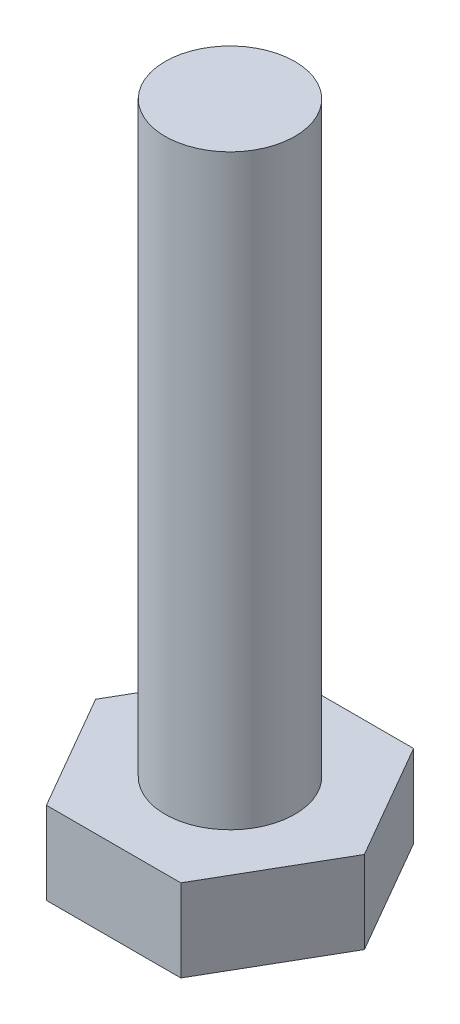
SolidWorks part; units mm, degrees
ref_plane "Front Plane" through (0, 0, 0) normal (0, 0, 1) x (1, 0, 0)
ref_plane "Top Plane" through (0, 0, 0) normal (0, 1, 0) x (1, 0, 0)
ref_plane "Right Plane" through (0, 0, 0) normal (1, 0, 0) x (0, 0, -1)
sketch "Sketch1" plane through (0, 0, 0) normal (0, 1, 0) x (1, 0, 0)
  line L0 (0, -5.65) -> (0, 5.65) construction
  line L3 (-3.262, 5.65) -> (3.262, 5.65)
  line L6 (-3.262, -5.65) -> (3.262, -5.65)
  line L9 (4.893, 2.825) -> (-4.893, -2.825) construction
  line L10 (6.5241, 0) -> (3.262, 5.65)
  line L11 (-3.262, -5.65) -> (-6.5241, 0)
  line L12 (-4.893, 2.825) -> (4.893, -2.825) construction
  line L13 (-3.262, 5.65) -> (-6.5241, 0)
  line L14 (6.5241, 0) -> (3.262, -5.65)
  point P3 (0, 0)
  point P7 (0, 5.65)
  point P10 (0, -5.65)
  point P24 (0, 0)
  dimension "D2" = 11.3
  dimension "D1" = 3
extrude "Boss-Extrude1" add sketch "Sketch1" along normal blind 4
sketch "Sketch2" plane through (0, 4, 0) normal (0, 1, 0) x (1, 0, 0)
  circle A0 centre (0, 0) radius 3.15
  dimension "D1" = 6.3
extrude "Boss-Extrude2" add sketch "Sketch2" along normal blind 28.5
ref_plane "Plane1" through (0, 25, 0) normal (0, 1, 0) x (1, 0, 0)
